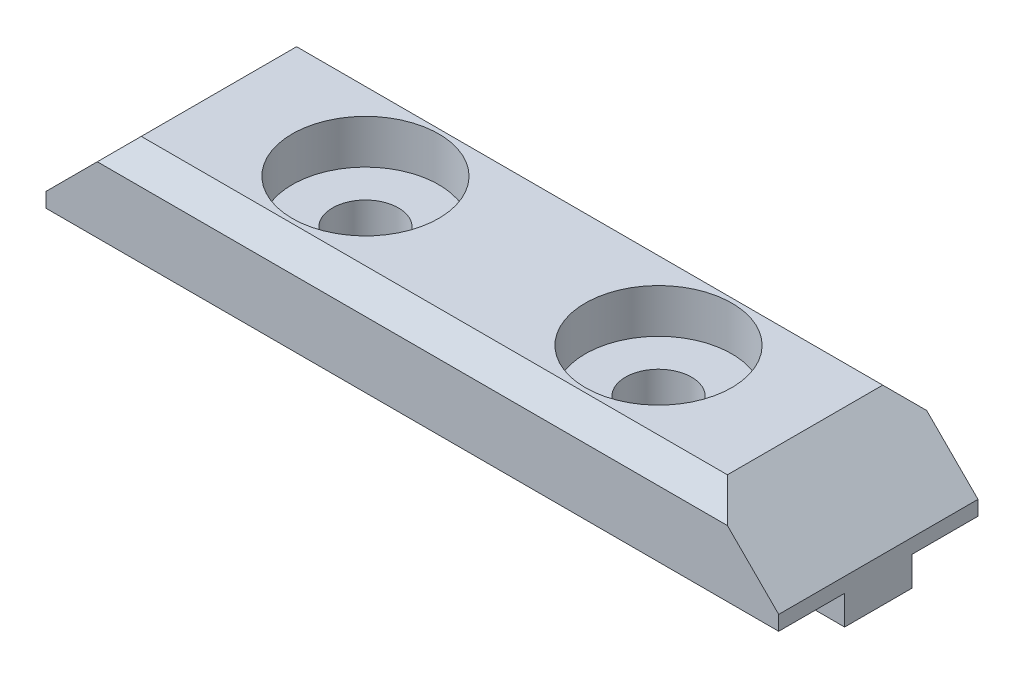
SolidWorks part; units mm, degrees
material "ABS generico"
ref_plane "Piano frontale" through (0, 0, 0) normal (0, 0, 1) x (1, 0, 0)
ref_plane "Piano superiore" through (0, 0, 0) normal (0, 1, 0) x (1, 0, 0)
ref_plane "Piano destro" through (0, 0, 0) normal (1, 0, 0) x (0, 0, -1)
sketch "Schizzo1" plane through (0, 0, 0) normal (1, 0, 0) x (0, 0, -1)
  line L0 (-2.3, 0) -> (2.3, 0)
  line L1 (2.3, 0) -> (2.3, 2)
  line L2 (2.3, 2) -> (6.8, 2)
  line L3 (6.8, 2) -> (6.8, 8)
  line L4 (6.8, 8) -> (-6.8, 8)
  line L5 (-6.8, 8) -> (-6.8, 2)
  line L6 (-6.8, 2) -> (-2.3, 2)
  line L7 (-2.3, 2) -> (-2.3, 0)
  point P4 (0, 0)
  dimension "D1" = 2
  dimension "D2" = 4.6
  dimension "D3" = 13.6
  dimension "D4" = 6
extrude "Estrusione-Estrusione1" add sketch "Schizzo1" along normal blind 50
chamfer "Smusso1" distance 1.5 angle 45 2 edges at (25, 8, -6.8) (25, 8, 6.8)
chamfer "Smusso2" distance 5 angle 45 2 edges at (50, 8, 0) (0, 8, 0)
hole_wizard "Foro lamato per Bullone M5 a testa esagonale-1" positions "Schizzo2" profile "Schizzo3" counterbore size "M5" standard "ISO"
sketch "Schizzo2" plane through (0, 8, 0) normal (0, 1, 0) x (1, 0, 0)
  line L0 (0, 0) -> (35, 0) construction
  line L2 (0, -6.8) -> (0, 6.8) construction
  point P0 (15, 0)
  point P2 (35, 0)
  dimension "D1" = 15
  dimension "D2" = 20
sketch "Schizzo3" plane through (15, 8, 0) normal (1, 0, 0) x (0, 0, 1)
  line L0 (0, 0) -> (0, 71.3519)
  line L1 (0, 71.3519) -> (2.25, 70)
  line L2 (2.25, 70) -> (2.25, 3)
  line L3 (2.25, 3) -> (5, 3)
  line L4 (5, 3) -> (5, 0)
  line L5 (5, 0) -> (0, 0)
  line L10 (0, 71.3519) -> (-2.25, 70) construction
  line L11 (0, -6.35) -> (0, 107.95) construction
  dimension "Hole Dia." = 4.5
  dimension "Hole Depth" = 70
  dimension "C'Bore Dia." = 10
  dimension "C'Bore Depth" = 3
  dimension "Drill Angle" = 118
